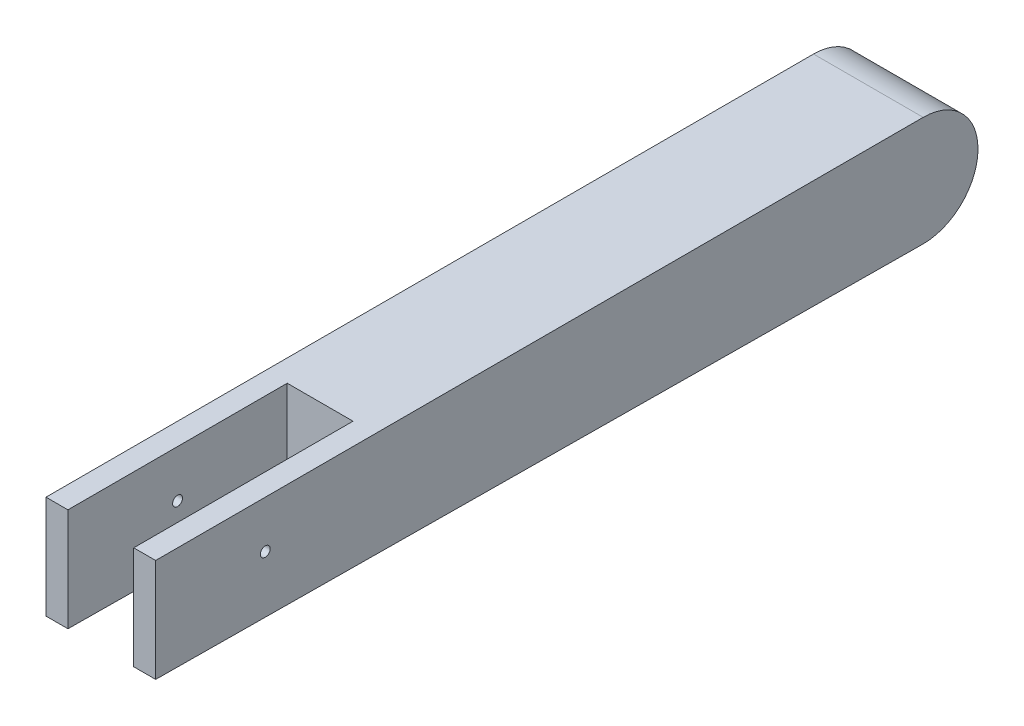
SolidWorks part; units mm, degrees
ref_plane "Front Plane" through (0, 0, 0) normal (0, 0, 1) x (1, 0, 0)
ref_plane "Top Plane" through (0, 0, 0) normal (0, 1, 0) x (1, 0, 0)
ref_plane "Right Plane" through (0, 0, 0) normal (1, 0, 0) x (0, 0, -1)
sketch "Sketch1" plane through (0, 0, 0) normal (1, 0, 0) x (0, 0, -1)
  line L0 (-209.8883, 35.419) -> (140.1117, 35.419)
  line L5 (140.1117, 35.419) -> (140.1117, -14.581)
  line L6 (140.1117, -14.581) -> (-209.8883, -11.5642)
  line L7 (-209.8883, -11.5642) -> (-209.8883, 13.4358)
  line L11 (-209.8883, 35.419) -> (-209.8883, 13.4358)
  circle A0 centre (140.1117, 10.419) radius 25
  dimension "D1" = 350
  dimension "D3" = 50
extrude "Boss-Extrude1" add sketch "Sketch1" along normal blind 50
sketch "Sketch5" plane through (50, 0, 0) normal (1, 0, 0) x (0, 0, -1)
  line L0 (-209.8883, -11.5642) -> (-209.8883, 35.419) construction
  circle A0 centre (-159.8883, 13.9451) radius 2.25
  dimension "D1" = 4.5
  dimension "D2" = 50
sketch "Sketch6" plane through (0, 35.419, 0) normal (0, 1, 0) x (1, 0, 0)
  line L0 (10, -209.8883) -> (10, -109.8883)
  line L1 (50, -209.8883) -> (0, -209.8883) construction
  line L2 (10, -109.8883) -> (40, -109.8883)
  line L3 (40, -109.8883) -> (40, -209.8883)
  line L4 (40, -209.8883) -> (10, -209.8883)
  line L5 (0, -209.8883) -> (0, 140.1117) construction
  dimension "D1" = 30
  dimension "D2" = 10
  dimension "D3" = 100
extrude "Cut-Extrude3" cut sketch "Sketch6" against normal through all
extrude "Cut-Extrude2" cut sketch "Sketch5" against normal through all
